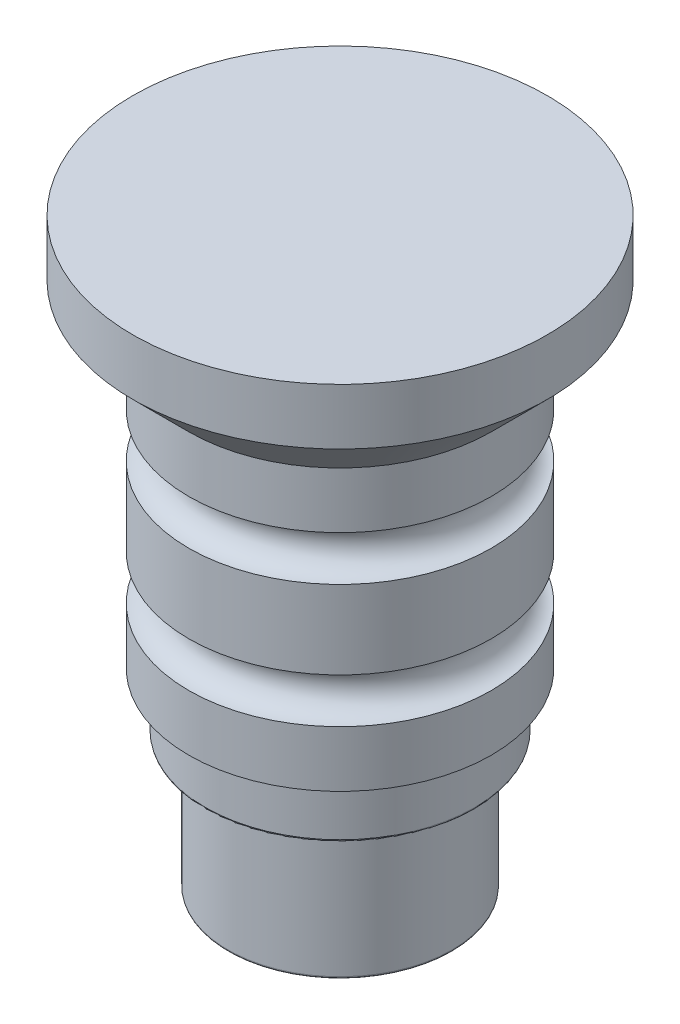
SolidWorks part; units mm, degrees
ref_plane "Plan de face" through (0, 0, 0) normal (0, 0, 1) x (1, 0, 0)
ref_plane "Plan de dessus" through (0, 0, 0) normal (0, 1, 0) x (1, 0, 0)
ref_plane "Plan de droite" through (0, 0, 0) normal (1, 0, 0) x (0, 0, -1)
sketch "Esquisse1" plane through (0, 0, 0) normal (0, 0, 1) x (1, 0, 0)
  line L1 (0, 0) -> (-7.5, 0)
  line L3 (-7.5, 0) -> (-10, 0)
  line L4 (-10, 0) -> (-10, 12)
  line L5 (-10, 12) -> (-12, 12)
  line L6 (-12, 12) -> (-12, 17)
  line L7 (-12, 17) -> (-13.5, 17)
  line L8 (-13.5, 17) -> (-13.5, 22)
  line L9 (-13.5, 26) -> (-13.5, 33)
  line L10 (-13.5, 37) -> (-13.5, 42)
  line L11 (-13.5, 42) -> (0, 42) construction
  line L12 (0, 42) -> (0, 0)
  line L20 (-13.5, 42) -> (0, 42) construction
  line L21 (-13.5, 42) -> (-18.5, 47)
  line L22 (-18.5, 47) -> (-18.5, 52)
  line L23 (-18.5, 52) -> (0, 52)
  line L24 (0, 52) -> (0, 42)
  arc A0 (-13.5, 37) -> (-13.5, 33) centre (-13.5, 35) cw
  arc A1 (-13.5, 26) -> (-13.5, 22) centre (-13.5, 24) cw
  dimension "D1" = 2
  dimension "D2" = 7
  dimension "D3" = 5
  dimension "D4" = 5
  dimension "D5" = 12
  dimension "D6" = 13.5
  dimension "D7" = 12
  dimension "D8" = 2.5
  dimension "D9" = 7.5
  dimension "D10" = 17
  dimension "D11" = 5
  dimension "D12" = 5
  dimension "D13" = 135
  dimension "D14" = 18.5
revolve "Révolution1" add sketch "Esquisse1" angle 360 about L12
fillet "Congé3" radius 0.2 3 edges at (-12, 12, 0) (-10, 12, 0) (-10, 0, 0)
